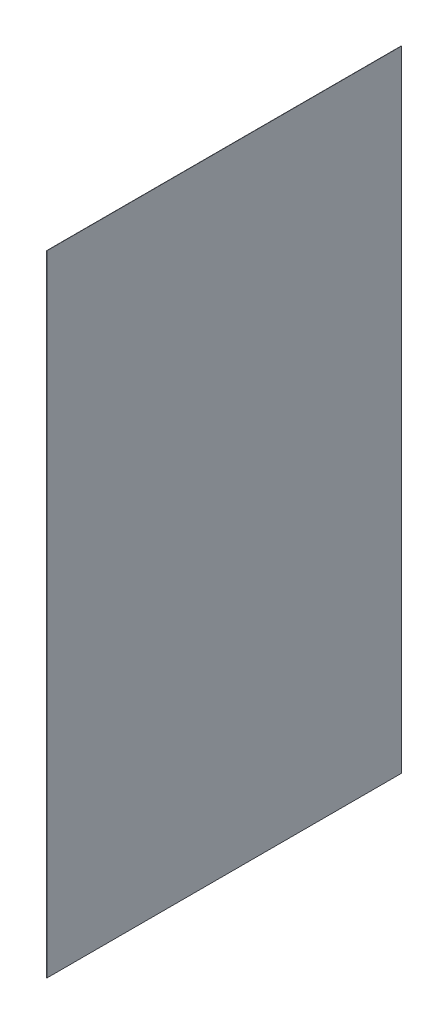
SolidWorks part; units mm, degrees
material "Polyester Resin"
ref_plane "Front Plane" through (0, 0, 0) normal (0, 0, 1) x (1, 0, 0)
ref_plane "Top Plane" through (0, 0, 0) normal (0, 1, 0) x (1, 0, 0)
ref_plane "Right Plane" through (0, 0, 0) normal (1, 0, 0) x (0, 0, -1)
sketch "Sketch1" plane through (0, 0, 0) normal (0, 0, 1) x (1, 0, 0)
  line L0 (0, 0.5) -> (0, -0.5) construction
  line L1 (0, 5) -> (0, 0) construction
  line L2 (-4.2633, 0) -> (-4.2633, 2.6123) construction
  line L3 (-5, 0) -> (0, 0) construction
  line L4 (0, 0) -> (20.4, 0) construction
  line L5 (-5.25, 0) -> (-5, 0)
  line L6 (-4.2633, 2.6123) -> (-4.2633, 3.0638)
  line L7 (20.4, 12.5) -> (20.4, -12.5) construction
  line L8 (-4.2633, 2.6123) -> (20.4, -12.5) construction
  line L9 (20.4, -12.5) -> (20.65, -12.5)
  line L10 (20.4, 0) -> (23.4, 0)
  line L11 (23.4, 0) -> (25.4, 0) construction
  line L12 (20.4, 0) -> (20.4, -12.5)
  line L13 (24.4, 12.5) -> (24.4, -12.5) construction
  line L14 (28.4, -12.5) -> (28.15, -12.5)
  line L15 (28.4, 0) -> (28.4, -12.5)
  line L16 (28.4, 0) -> (25.4, 0)
  line L17 (28.4, -12.5) -> (28.4, 12.5) construction
  line L18 (20.4, -12.5) -> (28.4, -12.5) construction
  line L19 (28.4, 0) -> (48.8, 0) construction
  line L20 (48.8, 0) -> (28.4, -12.5) construction
  line L21 (48.8, 0) -> (329.9959, 0) construction
  line L22 (329.9959, 254.635) -> (329.9959, -254.635) construction
  line L23 (679.9959, 310.1741) -> (679.9959, -310.1741) construction
  line L24 (679.9959, 0) -> (729.9959, 0) construction
  line L25 (729.9959, 254.635) -> (729.9959, -254.635)
  line L26 (679.9959, 254.635) -> (679.9959, 264.635)
  line L27 (329.9959, 254.635) -> (329.9959, -254.635)
  line L28 (329.9959, 0) -> (679.9959, 0) construction
  line L29 (679.9959, 254.635) -> (679.9959, -254.635)
  line L30 (679.9959, 310.1741) -> (48.8, 0) construction
  line L31 (329.9959, 254.635) -> (329.9959, 264.635)
  line L32 (329.9959, -254.635) -> (329.9959, -264.635)
  line L33 (679.9959, -254.635) -> (679.9959, -264.635)
  line L34 (679.9959, 254.635) -> (729.9959, 254.635) construction
  line L35 (729.9959, 0) -> (779.9959, 0) construction
  line L36 (779.9959, 254.635) -> (779.9959, -254.635)
  line L37 (729.9959, 254.635) -> (779.9959, 254.635) construction
  line L38 (779.9959, 254.635) -> (779.9959, 264.635)
  line L39 (779.9959, -254.635) -> (779.9959, -264.635)
  line L40 (779.9959, 0) -> (839.9959, 0) construction
  line L41 (839.9959, 0) -> (1095.4391, 0) construction
  line L42 (839.9959, -254.635) -> (839.9959, 254.635)
  line L43 (841.9959, -254.635) -> (841.9959, 254.635)
  line L44 (839.9959, 254.635) -> (839.9959, 264.635)
  line L45 (839.9959, 254.635) -> (841.9959, 254.635) construction
  line L46 (779.9959, 254.635) -> (1095.4391, 0) construction
  line L47 (841.9959, 254.635) -> (841.9959, 264.635)
  line L48 (1094.9959, 32.5) -> (1094.9959, -32.5)
  line L49 (1094.9959, 0) -> (3152.2686, 0) construction
  line L50 (3152.2686, -1435.2155) -> (3152.2686, 1435.2155)
  line L51 (1094.9959, 0) -> (729.9959, 254.635) construction
  line L52 (1094.9959, 0) -> (3152.2686, -1435.2155) construction
  line L53 (839.9959, -254.635) -> (839.9959, -264.635)
  line L54 (841.9959, -254.635) -> (841.9959, -264.635)
  line L55 (839.9959, -254.635) -> (841.9959, -254.635) construction
  line L56 (189.398, 119.0908) -> (189.398, -119.0908)
  line L57 (189.398, 119.0908) -> (189.398, 69.0908) construction
  arc A0 (0, -0.5) -> (0, 0.5) centre (0, 0) ccw construction
  arc A1 (0, 5) -> (-5, 0) centre (0, 0) ccw
  arc A2 (-4.2633, 3.0638) -> (-5.25, 0) centre (0, 0) ccw
  arc A3 (-4.2633, 2.6123) -> (-5, 0) centre (0, 0) ccw construction
  arc A4 (23.4, 0) -> (20.65, -12.5) centre (-6.3841, 0) cw
  arc A5 (25.4, 0) -> (28.15, -12.5) centre (55.1841, 0) ccw
  point P14 (20.4, 0)
  point P21 (24.4, 0)
  point P31 (329.9959, 0)
  point P38 (679.9959, 0)
  point P40 (729.9959, 0)
  point P48 (779.9959, 0)
  point P54 (839.9959, 0)
  point P62 (1094.9959, 0)
  point P64 (679.9959, 0)
  point P67 (189.398, 0)
  point P69 (3152.2686, 0)
  point P75 (189.398, 0)
  dimension "D1" = 1
  dimension "D4" = 0.25
  dimension "D2" = 0.25
  dimension "D3" = 5
  dimension "D5" = 3
  dimension "D6" = 2
  dimension "condenserFocalLength" = 20.4
  dimension "condenserDiameter" = 25
  dimension "D7" = 50
  dimension "D8" = 10
  dimension "D9" = 365
  dimension "fresnelCollectorFocus" = 350
  dimension "D10" = 281.1959
  dimension "D11" = 509.27
  dimension "D12" = 50
  dimension "D13" = 60
  dimension "D14" = 2
  dimension "D16" = 255.4432
  dimension "D17" = 65
  dimension "D19" = 620.3481
  dimension "D20" = 2057.2727
  dimension "D21" = 2870.4309
  dimension "D22" = 34.901
sketch "Sketch4" plane through (0, 0, 0) normal (0, 1, 0) x (1, 0, 0)
  line L0 (0, 0.5) -> (0, -0.5) construction
  line L1 (0, 5) -> (0, 0) construction
  line L2 (-4.2633, 0) -> (-4.2633, 2.6123) construction
  line L3 (-5, 0) -> (0, 0) construction
  line L4 (0, 0) -> (20.4, 0) construction
  line L5 (-5.25, 0) -> (-5, 0)
  line L6 (-4.2633, 2.6123) -> (-4.2633, 3.0638)
  line L7 (20.4, 12.5) -> (20.4, -12.5) construction
  line L8 (-4.2633, 2.6123) -> (20.4, -12.5) construction
  line L9 (20.4, -12.5) -> (20.65, -12.5)
  line L10 (20.4, 0) -> (23.4, 0)
  line L11 (23.4, 0) -> (25.4, 0) construction
  line L12 (20.4, 0) -> (20.4, -12.5)
  line L13 (24.4, 12.5) -> (24.4, -12.5) construction
  line L14 (28.4, -12.5) -> (28.15, -12.5)
  line L15 (28.4, 0) -> (28.4, -12.5)
  line L16 (28.4, 0) -> (25.4, 0)
  line L17 (28.4, -12.5) -> (28.4, 12.5) construction
  line L18 (20.4, -12.5) -> (28.4, -12.5) construction
  line L19 (28.4, 0) -> (48.8, 0) construction
  line L20 (48.8, 0) -> (28.4, -12.5) construction
  line L21 (48.8, 0) -> (329.9959, 0) construction
  line L22 (329.9959, 143.256) -> (329.9959, -143.256) construction
  line L23 (679.9959, 310.1741) -> (679.9959, -310.1741) construction
  line L24 (679.9959, 0) -> (729.9959, 0) construction
  line L25 (729.9959, 143.256) -> (729.9959, -143.256)
  line L26 (679.9959, 143.256) -> (679.9959, 153.256)
  line L27 (329.9959, 143.256) -> (329.9959, -143.256)
  line L28 (329.9959, 0) -> (679.9959, 0) construction
  line L29 (679.9959, 143.256) -> (679.9959, -143.256)
  line L30 (679.9959, 310.1741) -> (48.8, 0) construction
  line L31 (329.9959, 143.256) -> (329.9959, 153.256)
  line L32 (329.9959, -143.256) -> (329.9959, -153.256)
  line L33 (679.9959, -143.256) -> (679.9959, -153.256)
  line L34 (679.9959, 143.256) -> (729.9959, 143.256) construction
  line L35 (729.9959, 0) -> (779.9959, 0) construction
  line L36 (779.9959, 143.256) -> (779.9959, -143.256)
  line L37 (729.9959, 143.256) -> (779.9959, 143.256) construction
  line L38 (779.9959, 143.256) -> (779.9959, 153.256)
  line L39 (779.9959, -143.256) -> (779.9959, -153.256)
  line L40 (779.9959, 0) -> (839.9959, 0) construction
  line L41 (839.9959, 0) -> (1095.4391, 0) construction
  line L42 (839.9959, -143.256) -> (839.9959, 143.256)
  line L43 (841.9959, -143.256) -> (841.9959, 143.256)
  line L44 (839.9959, 143.256) -> (839.9959, 153.256)
  line L45 (839.9959, 143.256) -> (841.9959, 143.256) construction
  line L46 (779.9959, 143.256) -> (1095.4391, 0) construction
  line L47 (841.9959, 143.256) -> (841.9959, 153.256)
  line L48 (1094.9959, 32.5) -> (1094.9959, -32.5)
  line L49 (1094.9959, 0) -> (3152.2686, 0) construction
  line L50 (3152.2686, -807.4429) -> (3152.2686, 807.4429)
  line L51 (1094.9959, 0) -> (729.9959, 143.256) construction
  line L52 (1094.9959, 0) -> (3152.2686, -807.4429) construction
  line L53 (839.9959, -143.256) -> (839.9959, -153.256)
  line L54 (841.9959, -143.256) -> (841.9959, -153.256)
  line L55 (839.9959, -143.256) -> (841.9959, -143.256) construction
  line L56 (189.398, 119.0908) -> (189.398, -119.0908)
  line L57 (189.398, 119.0908) -> (189.398, 69.0908) construction
  arc A0 (0, -0.5) -> (0, 0.5) centre (0, 0) ccw construction
  arc A1 (0, 5) -> (-5, 0) centre (0, 0) ccw
  arc A2 (-4.2633, 3.0638) -> (-5.25, 0) centre (0, 0) ccw
  arc A3 (-4.2633, 2.6123) -> (-5, 0) centre (0, 0) ccw construction
  arc A4 (23.4, 0) -> (20.65, -12.5) centre (-6.3841, 0) cw
  arc A5 (25.4, 0) -> (28.15, -12.5) centre (55.1841, 0) ccw
  point P14 (20.4, 0)
  point P21 (24.4, 0)
  point P31 (329.9959, 0)
  point P38 (679.9959, 0)
  point P40 (729.9959, 0)
  point P48 (779.9959, 0)
  point P54 (839.9959, 0)
  point P62 (1094.9959, 0)
  point P64 (679.9959, 0)
  point P67 (189.398, 0)
  point P69 (3152.2686, 0)
  point P75 (189.398, 0)
  dimension "D1" = 1
  dimension "D4" = 0.25
  dimension "D2" = 0.25
  dimension "D3" = 5
  dimension "D5" = 3
  dimension "D6" = 2
  dimension "condenserFocalLength" = 20.4
  dimension "condenserDiameter" = 25
  dimension "D7" = 50
  dimension "D8" = 10
  dimension "D9" = 281.1959
  dimension "D10" = 350
  dimension "D11" = 286.512
  dimension "D12" = 50
  dimension "D13" = 60
  dimension "D14" = 2
  dimension "D15" = 365
  dimension "D16" = 255.4432
  dimension "D17" = 65
  dimension "D19" = 620.3481
  dimension "D20" = 2057.2727
  dimension "D21" = 1614.8858
  dimension "D22" = 21.429
sketch3d "3DSketch1"
  line L1 (3152.2686, 1435.2155, 807.4429) -> (3152.2686, -1435.2155, 807.4429)
  line L2 (3152.2686, 1435.2155, 807.4429) -> (3152.2686, 1435.2155, -807.4429)
  line L3 (3152.2686, 1435.2155, -807.4429) -> (3152.2686, -1435.2155, -807.4429)
  line L4 (3152.2686, -1435.2155, 807.4429) -> (3152.2686, -1435.2155, -807.4429)
extrude "Boss-Extrude1" add sketch "3DSketch1" along direction (1, 0, 0) on the side of the normal blind 1
equation "\"colF2\"= 787.4"
equation "\"colF1\"= 787.4"
equation "\"colD\"= 350"
equation "\"colEFL\"= ( ( 1 / \"colF2\" ) + 1 / ( \"colF1\" ) - \"colD\" / ( \"colF2\" * \"colF1\" ) ) ^ - 1"
equation "\"fresnelCollectorFocus@Sketch1\"=\"colD\""
equation "\"D13@Sketch1\"=\"conD\""
equation "\"colBFL\"= ( ( \"colF2\" * ( \"colD\" - \"colF1\" ) ) / ( \"colD\" - ( \"colF1\" + \"colF2\" ) ) )"
equation "\"conD\"= 60"
equation "\"conF1\"= 787.4"
equation "\"conF2\"= 787.4/2"
equation "\"conEFL\"= ( ( - 1 * \"conF1\" * \"conF2\" ) / ( \"conD\" - \"conF1\" - \"conF2\" ) )"
equation "\"conBFL\"= ( ( \"conF2\" * ( \"conD\" - \"conF1\" ) ) / ( \"conD\" - ( \"conF1\" + \"conF2\" ) ) )"
equation "\"D16@Sketch1\"=\"conBFL\""
equation "\"condenserEFL\"= 20.40"
equation "\"condenserDiameter\"= 25"
equation "\"colBEAM\"= \"condenserDiameter\" * ( \"colEFL\" / \"condenserEFL\" )"
equation "\"D19@Sketch1\"=\"colBEAM\""
equation "\"projectorFL\"= 310'Condition: LCD Distance > projectorFL"
equation "\"LCD_Distance\"= 365"
equation "\"imageDistance\"= ( ( \"LCD_Distance\" * \"projectorFL\" ) / ( \"LCD_Distance\" - \"projectorFL\" ) )"
equation "\"D20@Sketch1\" = \"imageDistance\""
equation "\"D10@Sketch1\" = \"colBFL\""
equation "\"condenserFocalLength@Sketch1\"=\"condenserEFL\""
equation "\"condenserDiameter@Sketch1\"=\"condenserDiameter\""
equation "\"D9@Sketch4\"=\"colBFL\""
equation "\"D10@Sketch4\"=\"colD\""
equation "\"condenserFocalLength@Sketch4\"=\"condenserEFL\""
equation "\"condenserDiameter@Sketch4\"=\"condenserDiameter\""
equation "\"D19@Sketch4\"=\"colBEAM\""
equation "\"D13@Sketch4\"=\"conD\""
equation "\"D16@Sketch4\"=\"conBFL\""
equation "\"D20@Sketch4\" = \"imageDistance\""
equation "\"D15@Sketch4\"=\"LCD_Distance\""
equation "\"D9@Sketch1\"=\"LCD_Distance\""
